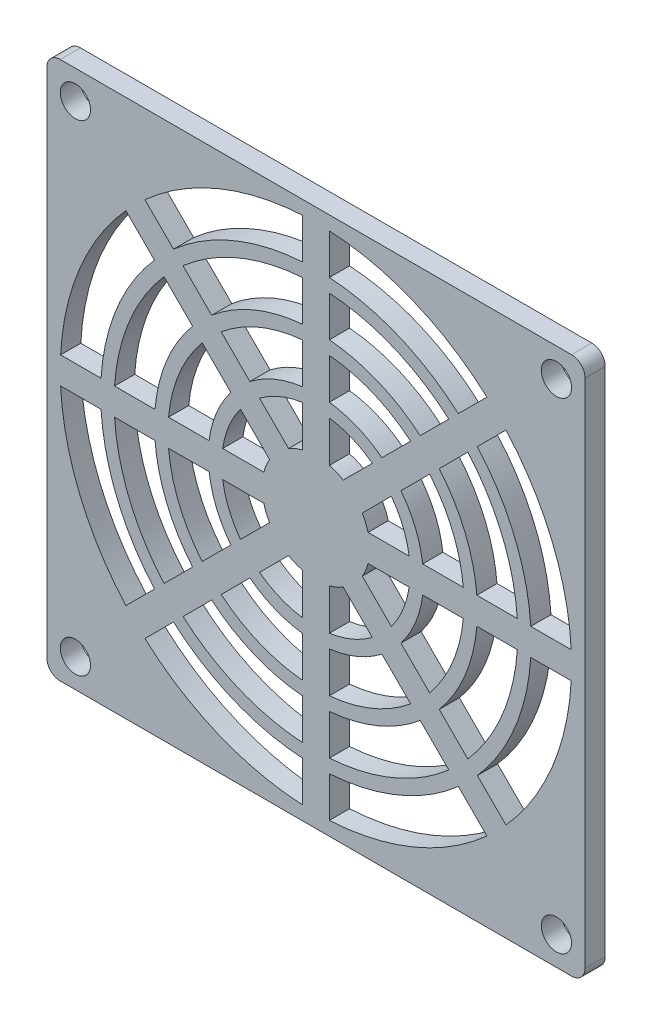
SolidWorks part; units mm, degrees
ref_plane "前视基准面" through (0, 0, 0) normal (0, 0, 1) x (1, 0, 0)
ref_plane "上视基准面" through (0, 0, 0) normal (0, 1, 0) x (1, 0, 0)
ref_plane "右视基准面" through (0, 0, 0) normal (1, 0, 0) x (0, 0, -1)
sketch "草图1" plane through (0, 0, 0) normal (0, 0, 1) x (1, 0, 0)
  line L1 (-38, -40) -> (38, -40)
  line L2 (-40, -38) -> (-40, 38)
  line L3 (-38, 40) -> (38, 40)
  line L4 (40, -38) -> (40, 38)
  line L5 (-40, -40) -> (40, 40) construction
  line L6 (-40, 40) -> (40, -40) construction
  line L7 (-35.75, -35.75) -> (35.75, -35.75) construction
  line L8 (-35.75, -35.75) -> (-35.75, 35.75) construction
  line L9 (-35.75, 35.75) -> (35.75, 35.75) construction
  line L10 (35.75, -35.75) -> (35.75, 35.75) construction
  line L11 (-35.75, -35.75) -> (35.75, 35.75) construction
  line L12 (-35.75, 35.75) -> (35.75, -35.75) construction
  line L13 (-1.9141, -40) -> (2.0859, -40) construction
  line L17 (-1.9141, 40) -> (2.0859, 40) construction
  line L19 (2, 37.9473) -> (2, 31.9374)
  line L20 (2, 40) -> (2, -2) construction
  line L22 (0, 40) -> (0, 0) construction
  line L24 (35.2269, 38.0553) -> (-37.3422, -34.5138) construction
  line L26 (2, 29.9333) -> (2, 23.9165)
  line L28 (2, 21.9089) -> (2, 15.8745)
  line L30 (25.4186, 28.247) -> (21.169, 23.9974)
  line L32 (19.7518, 22.5802) -> (15.4973, 18.3257)
  line L33 (14.0777, 16.9061) -> (9.8108, 12.6392)
  line L36 (37.9473, 2) -> (31.9374, 2)
  line L37 (28.247, 25.4186) -> (23.9974, 21.169)
  line L38 (29.9333, 2) -> (23.9165, 2)
  line L39 (22.5802, 19.7518) -> (18.3257, 15.4973)
  line L40 (21.9089, 2) -> (15.8745, 2)
  line L41 (16.9061, 14.0777) -> (12.6392, 9.8108)
  line L42 (28.247, -25.4186) -> (23.9974, -21.169)
  line L43 (37.9473, -2) -> (31.9374, -2)
  line L44 (22.5802, -19.7518) -> (18.3257, -15.4973)
  line L45 (29.9333, -2) -> (23.9165, -2)
  line L46 (16.9061, -14.0777) -> (12.6392, -9.8108)
  line L47 (21.9089, -2) -> (15.8745, -2)
  line L48 (2, -37.9473) -> (2, -31.9374)
  line L49 (25.4186, -28.247) -> (21.169, -23.9974)
  line L50 (2, -29.9333) -> (2, -23.9165)
  line L51 (19.7518, -22.5802) -> (15.4973, -18.3257)
  line L52 (2, -21.9089) -> (2, -15.8745)
  line L53 (14.0777, -16.9061) -> (9.8108, -12.6392)
  line L54 (-25.4186, -28.247) -> (-21.169, -23.9974)
  line L55 (-2, -37.9473) -> (-2, -31.9374)
  line L56 (-19.7518, -22.5802) -> (-15.4973, -18.3257)
  line L57 (-2, -29.9333) -> (-2, -23.9165)
  line L58 (-14.0777, -16.9061) -> (-9.8108, -12.6392)
  line L59 (-2, -21.9089) -> (-2, -15.8745)
  line L60 (-37.9473, -2) -> (-31.9374, -2)
  line L61 (-28.247, -25.4186) -> (-23.9974, -21.169)
  line L62 (-29.9333, -2) -> (-23.9165, -2)
  line L63 (-22.5802, -19.7518) -> (-18.3257, -15.4973)
  line L64 (-21.9089, -2) -> (-15.8745, -2)
  line L65 (-16.9061, -14.0777) -> (-12.6392, -9.8108)
  line L66 (-28.247, 25.4186) -> (-23.9974, 21.169)
  line L67 (-37.9473, 2) -> (-31.9374, 2)
  line L68 (-22.5802, 19.7518) -> (-18.3257, 15.4973)
  line L69 (-29.9333, 2) -> (-23.9165, 2)
  line L70 (-16.9061, 14.0777) -> (-12.6392, 9.8108)
  line L71 (-21.9089, 2) -> (-15.8745, 2)
  line L72 (-2, 37.9473) -> (-2, 31.9374)
  line L73 (-25.4186, 28.247) -> (-21.169, 23.9974)
  line L74 (-2, 29.9333) -> (-2, 23.9165)
  line L75 (-19.7518, 22.5802) -> (-15.4973, 18.3257)
  line L76 (-2, 21.9089) -> (-2, 15.8745)
  line L77 (-14.0777, 16.9061) -> (-9.8108, 12.6392)
  line L78 (8.3837, 11.2122) -> (4.063, 6.8914)
  line L79 (2, 13.8564) -> (2, 7.746)
  line L81 (11.2122, 8.3837) -> (6.8914, 4.063)
  line L82 (13.8564, 2) -> (7.746, 2)
  line L83 (13.8564, -2) -> (7.746, -2)
  line L84 (11.2122, -8.3837) -> (6.8914, -4.063)
  line L85 (8.3837, -11.2122) -> (4.063, -6.8914)
  line L86 (2, -13.8564) -> (2, -7.746)
  line L87 (-2, -13.8564) -> (-2, -7.746)
  line L88 (-8.3837, -11.2122) -> (-4.063, -6.8914)
  line L89 (-11.2122, -8.3837) -> (-6.8914, -4.063)
  line L90 (-13.8564, -2) -> (-7.746, -2)
  line L91 (-13.8564, 2) -> (-7.746, 2)
  line L92 (-11.2122, 8.3837) -> (-6.8914, 4.063)
  line L93 (-8.3837, 11.2122) -> (-4.063, 6.8914)
  line L94 (-2, 13.8564) -> (-2, 7.746)
  circle A0 centre (-35.75, 35.75) radius 2.25
  circle A1 centre (35.75, 35.75) radius 2.25
  circle A2 centre (35.75, -35.75) radius 2.25
  circle A3 centre (-35.75, -35.75) radius 2.25
  arc A4 (38, 40) -> (40, 38) centre (38, 38) cw
  arc A5 (38, -40) -> (40, -38) centre (38, -38) ccw
  arc A6 (-38, -40) -> (-40, -38) centre (-38, -38) cw
  arc A7 (-40, 38) -> (-38, 40) centre (-38, 38) cw
  arc A12 (25.4186, 28.247) -> (2, 37.9473) centre (0, 0) ccw
  arc A21 (19.7518, 22.5802) -> (2, 29.9333) centre (0, 0) ccw
  arc A22 (21.169, 23.9974) -> (2, 31.9374) centre (0, 0) ccw
  arc A23 (15.4973, 18.3257) -> (2, 23.9165) centre (0, 0) ccw
  arc A27 (14.0777, 16.9061) -> (2, 21.9089) centre (0, 0) ccw
  arc A28 (2, 15.8745) -> (9.8108, 12.6392) centre (0, 0) cw
  arc A29 (31.9374, 2) -> (23.9974, 21.169) centre (0, 0) ccw
  arc A30 (37.9473, 2) -> (28.247, 25.4186) centre (0, 0) ccw
  arc A31 (23.9165, 2) -> (18.3257, 15.4973) centre (0, 0) ccw
  arc A32 (29.9333, 2) -> (22.5802, 19.7518) centre (0, 0) ccw
  arc A33 (12.6392, 9.8108) -> (15.8745, 2) centre (0, 0) cw
  arc A34 (21.9089, 2) -> (16.9061, 14.0777) centre (0, 0) ccw
  arc A35 (23.9974, -21.169) -> (31.9374, -2) centre (0, 0) ccw
  arc A36 (28.247, -25.4186) -> (37.9473, -2) centre (0, 0) ccw
  arc A37 (18.3257, -15.4973) -> (23.9165, -2) centre (0, 0) ccw
  arc A38 (22.5802, -19.7518) -> (29.9333, -2) centre (0, 0) ccw
  arc A39 (15.8745, -2) -> (12.6392, -9.8108) centre (0, 0) cw
  arc A40 (16.9061, -14.0777) -> (21.9089, -2) centre (0, 0) ccw
  arc A41 (2, -31.9374) -> (21.169, -23.9974) centre (0, 0) ccw
  arc A42 (2, -37.9473) -> (25.4186, -28.247) centre (0, 0) ccw
  arc A43 (2, -23.9165) -> (15.4973, -18.3257) centre (0, 0) ccw
  arc A44 (2, -29.9333) -> (19.7518, -22.5802) centre (0, 0) ccw
  arc A45 (9.8108, -12.6392) -> (2, -15.8745) centre (0, 0) cw
  arc A46 (2, -21.9089) -> (14.0777, -16.9061) centre (0, 0) ccw
  arc A47 (-21.169, -23.9974) -> (-2, -31.9374) centre (0, 0) ccw
  arc A48 (-25.4186, -28.247) -> (-2, -37.9473) centre (0, 0) ccw
  arc A49 (-15.4973, -18.3257) -> (-2, -23.9165) centre (0, 0) ccw
  arc A50 (-19.7518, -22.5802) -> (-2, -29.9333) centre (0, 0) ccw
  arc A51 (-2, -15.8745) -> (-9.8108, -12.6392) centre (0, 0) cw
  arc A52 (-14.0777, -16.9061) -> (-2, -21.9089) centre (0, 0) ccw
  arc A53 (-31.9374, -2) -> (-23.9974, -21.169) centre (0, 0) ccw
  arc A54 (-37.9473, -2) -> (-28.247, -25.4186) centre (0, 0) ccw
  arc A55 (-23.9165, -2) -> (-18.3257, -15.4973) centre (0, 0) ccw
  arc A56 (-29.9333, -2) -> (-22.5802, -19.7518) centre (0, 0) ccw
  arc A57 (-12.6392, -9.8108) -> (-15.8745, -2) centre (0, 0) cw
  arc A58 (-21.9089, -2) -> (-16.9061, -14.0777) centre (0, 0) ccw
  arc A59 (-23.9974, 21.169) -> (-31.9374, 2) centre (0, 0) ccw
  arc A60 (-28.247, 25.4186) -> (-37.9473, 2) centre (0, 0) ccw
  arc A61 (-18.3257, 15.4973) -> (-23.9165, 2) centre (0, 0) ccw
  arc A62 (-22.5802, 19.7518) -> (-29.9333, 2) centre (0, 0) ccw
  arc A63 (-15.8745, 2) -> (-12.6392, 9.8108) centre (0, 0) cw
  arc A64 (-16.9061, 14.0777) -> (-21.9089, 2) centre (0, 0) ccw
  arc A65 (-2, 31.9374) -> (-21.169, 23.9974) centre (0, 0) ccw
  arc A66 (-2, 37.9473) -> (-25.4186, 28.247) centre (0, 0) ccw
  arc A67 (-2, 23.9165) -> (-15.4973, 18.3257) centre (0, 0) ccw
  arc A68 (-2, 29.9333) -> (-19.7518, 22.5802) centre (0, 0) ccw
  arc A69 (-9.8108, 12.6392) -> (-2, 15.8745) centre (0, 0) cw
  arc A70 (-2, 21.9089) -> (-14.0777, 16.9061) centre (0, 0) ccw
  arc A71 (2, 13.8564) -> (8.3837, 11.2122) centre (0, 0) cw
  arc A72 (2, 7.746) -> (4.063, 6.8914) centre (0, 0) cw
  arc A73 (6.8914, 4.063) -> (7.746, 2) centre (0, 0) cw
  arc A74 (11.2122, 8.3837) -> (13.8564, 2) centre (0, 0) cw
  arc A75 (7.746, -2) -> (6.8914, -4.063) centre (0, 0) cw
  arc A76 (13.8564, -2) -> (11.2122, -8.3837) centre (0, 0) cw
  arc A77 (4.063, -6.8914) -> (2, -7.746) centre (0, 0) cw
  arc A78 (8.3837, -11.2122) -> (2, -13.8564) centre (0, 0) cw
  arc A79 (-2, -7.746) -> (-4.063, -6.8914) centre (0, 0) cw
  arc A80 (-2, -13.8564) -> (-8.3837, -11.2122) centre (0, 0) cw
  arc A81 (-6.8914, -4.063) -> (-7.746, -2) centre (0, 0) cw
  arc A82 (-11.2122, -8.3837) -> (-13.8564, -2) centre (0, 0) cw
  arc A83 (-7.746, 2) -> (-6.8914, 4.063) centre (0, 0) cw
  arc A84 (-13.8564, 2) -> (-11.2122, 8.3837) centre (0, 0) cw
  arc A85 (-4.063, 6.8914) -> (-2, 7.746) centre (0, 0) cw
  arc A86 (-8.3837, 11.2122) -> (-2, 13.8564) centre (0, 0) cw
  point P0 (0, 0)
  point P6 (0, 0)
  point P30 (0, 0)
  point P36 (0, 0)
  dimension "D5" = 4.5
  dimension "D8" = 2
  dimension "D9" = 6
  dimension "D10" = 2
  dimension "D11" = 2
  dimension "D12" = 38
  dimension "D13" = 2
  dimension "D15" = 2
  dimension "D16" = 6
  dimension "D17" = 8
  dimension "D14" = 6
  dimension "D19" = 2
  dimension "D20" = 6
  dimension "D1" = 80
  dimension "D2" = 80
  dimension "D3" = 71.5
  dimension "D4" = 71.5
  dimension "D18" = 2
  dimension "D6" = 2
  dimension "D7" = 2
  dimension "D21" = 8
extrude "凸台-拉伸1" add sketch "草图1" along normal blind 3
